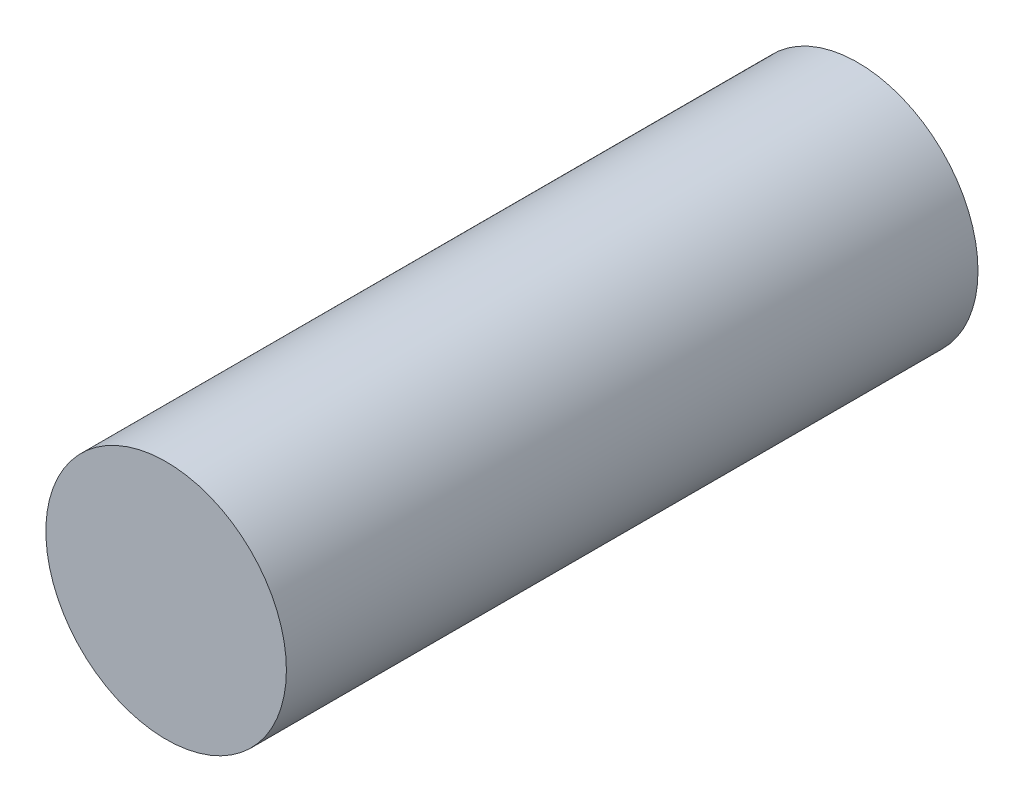
SolidWorks part; units mm, degrees
material "Stainless Steel (ferritic)"
ref_plane "Front Plane" through (0, 0, 0) normal (0, 0, 1) x (1, 0, 0)
ref_plane "Top Plane" through (0, 0, 0) normal (0, 1, 0) x (1, 0, 0)
ref_plane "Right Plane" through (0, 0, 0) normal (1, 0, 0) x (0, 0, -1)
sketch "Sketch1" plane through (0, 0, 0) normal (0, 0, 1) x (1, 0, 0)
  circle A0 centre (0, 0) radius 6.35
  dimension "D1" = 12.7
extrude "Boss-Extrude1" add sketch "Sketch1" along normal blind 36.5125
